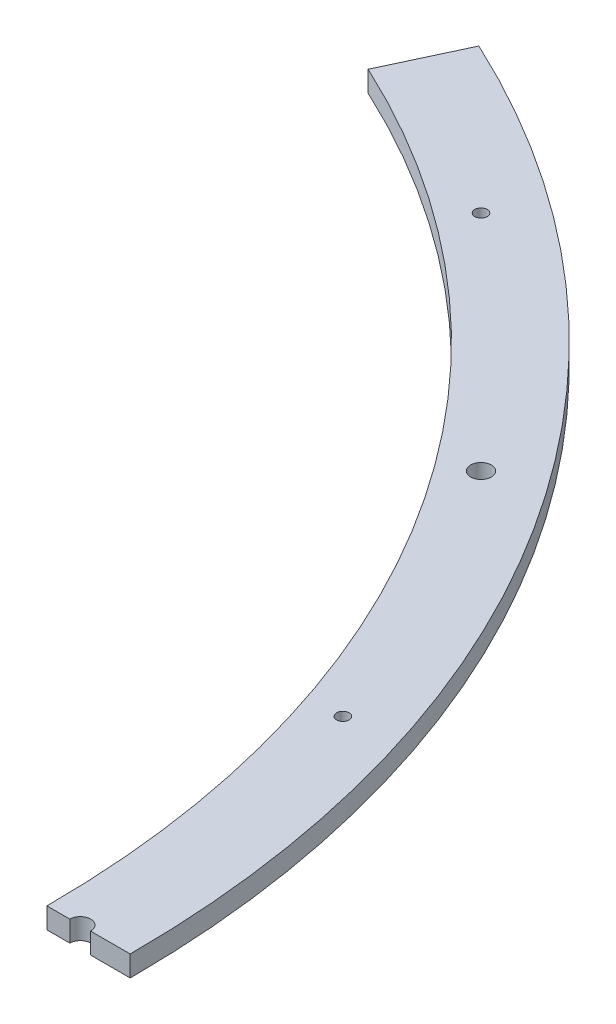
SolidWorks part; units mm, degrees
ref_plane "Front Plane" through (0, 0, 0) normal (0, 0, 1) x (1, 0, 0)
ref_plane "Top Plane" through (0, 0, 0) normal (0, 1, 0) x (1, 0, 0)
ref_plane "Right Plane" through (0, 0, 0) normal (1, 0, 0) x (0, 0, -1)
sketch "Sketch1" plane through (0, 0, 0) normal (0, 1, 0) x (1, 0, 0)
  circle A0 centre (0, 0) radius 254.5
  circle A1 centre (0, 0) radius 234.5
extrude "Boss-Extrude1" add sketch "Sketch1" along normal blind 5
sketch "Sketch2" plane through (0, 5, 0) normal (0, 1, 0) x (1, 0, 0)
  line L0 (-254.5, 0) -> (-226.6942, 0)
  line L1 (-226.6942, 0) -> (-226.6942, 60)
  line L2 (-226.6942, 60) -> (-254.5, 60)
  line L3 (-254.5, 60) -> (-254.5, 0)
  circle A0 centre (0, 0) radius 254.5 construction
  circle A1 centre (0, 0) radius 234.5 construction
  dimension "D1" = 60
extrude "Cut-Extrude1" cut sketch "Sketch2" against normal blind 5
mirror "Mirror1" about plane through (0, 0, 0) normal (0, 0, 1) of "Cut-Extrude1"
sketch "Sketch3" plane through (0, 5, 0) normal (0, 1, 0) x (1, 0, 0)
  circle A0 centre (242.5, 0) radius 2.5
  circle A1 centre (196.1866, -142.5379) radius 2.5
  circle A2 centre (74.9366, -230.6312) radius 2.5
  circle A3 centre (-74.9366, -230.6312) radius 2.5
  circle A4 centre (-196.1866, -142.5379) radius 2.5
  circle A5 centre (-242.5, 0) radius 2.5
  circle A6 centre (-196.1866, 142.5379) radius 2.5
  circle A7 centre (-74.9366, 230.6312) radius 2.5
  circle A8 centre (74.9366, 230.6312) radius 2.5
  circle A9 centre (196.1866, 142.5379) radius 2.5
  point P23 (0, 0)
  dimension "D1" = 242.5
  dimension "D2" = 10
extrude "Cut-Extrude2" cut sketch "Sketch3" against normal blind 5
sketch "Sketch4" plane through (0, 5, 0) normal (0, 1, 0) x (1, 0, 0)
  arc A0 (196.1866, 142.5379) -> (242.5, 0) centre (0, 0) cw
  circle A1 centre (230.6312, 74.9366) radius 1.5
  circle A2 centre (230.6312, -74.9366) radius 1.5
  circle A3 centre (142.5379, -196.1866) radius 1.5
  circle A4 centre (0, -242.5) radius 1.5
  circle A5 centre (-142.5379, -196.1866) radius 1.5
  circle A6 centre (-230.6312, -74.9366) radius 1.5
  circle A7 centre (-230.6312, 74.9366) radius 1.5
  circle A8 centre (-142.5379, 196.1866) radius 1.5
  circle A9 centre (0, 242.5) radius 1.5
  circle A10 centre (142.5379, 196.1866) radius 1.5
  circle A11 centre (230.6312, -74.9366) radius 1.5
  circle A12 centre (142.5379, -196.1866) radius 1.5
  circle A13 centre (0, -242.5) radius 1.5
  circle A14 centre (-142.5379, -196.1866) radius 1.5
  circle A15 centre (-230.6312, -74.9366) radius 1.5
  circle A16 centre (-230.6312, 74.9366) radius 1.5
  circle A17 centre (-142.5379, 196.1866) radius 1.5
  circle A18 centre (0, 242.5) radius 1.5
  circle A19 centre (142.5379, 196.1866) radius 1.5
  point P28 (0, 0)
  point P47 (0, 0)
  dimension "D1" = 10
  dimension "D2" = 10
extrude "Cut-Extrude3" cut sketch "Sketch4" against normal blind 5 contours A4 | A5 | A6 | A7 | A8 | A9 | A10 | A1 | A2 | A3
sketch "Sketch5" plane through (0, 5, 0) normal (0, 1, 0) x (1, 0, 0)
  line L1 (254.5, 0) -> (-396.7126, 0)
  line L2 (254.5, 0) -> (254.5, -357.2264)
  line L3 (254.5, -357.2264) -> (-396.7126, -357.2264)
  line L4 (-396.7126, 0) -> (-396.7126, -357.2264)
  arc A0 (-247.3262, -60) -> (-247.3262, 60) centre (0, 0) ccw construction
extrude "Cut-Extrude4" cut sketch "Sketch5" against normal blind 10
sketch "Sketch6" plane through (0, 5, 0) normal (0, 1, 0) x (1, 0, 0)
  line L0 (254.5, 0) -> (0, 0)
  line L1 (0, 0) -> (-127.25, 220.4035)
  line L2 (0, 0) -> (-254.5, 0)
  arc A0 (-127.25, 220.4035) -> (254.5, 0) centre (0, 0) cw
  arc A1 (254.5, 0) -> (-247.3262, 60) centre (0, 0) ccw construction
  arc A2 (-127.25, 220.4035) -> (-254.5, 0) centre (0, 0) ccw
  arc M5 (254.5, 0) -> (-247.3262, 60) centre (0, 0) ccw
  line M6 (-247.3262, 60) -> (-226.6942, 60)
  arc M7 (-226.6942, 60) -> (234.5, 0) centre (0, 0) cw
  circle M13 centre (-142.5379, 196.1866) radius 1.5
  circle M14 centre (-230.6312, 74.9366) radius 1.5
  circle M18 centre (-196.1866, 142.5379) radius 2.5
  dimension "D1" = 120
extrude "Cut-Extrude9" cut sketch "Sketch6" against normal blind 10 contours L1 M7 M5 M6 M13 M18 M14 | A2 L2 L1 M6 M7
sketch "Sketch7" plane through (0, 5, 0) normal (0, 1, 0) x (1, 0, 0)
  line L0 (254.5, 0) -> (0, 0)
  line L1 (0, 0) -> (107.5563, 230.6553)
  line L2 (0, 0) -> (-127.25, 220.4035)
  arc A0 (107.5563, 230.6553) -> (254.5, 0) centre (0, 0) cw
  arc A1 (254.5, 0) -> (-127.25, 220.4035) centre (0, 0) ccw construction
  line M4 (-127.25, 220.4035) -> (-117.25, 203.083)
  arc M5 (-117.25, 203.083) -> (234.5, 0) centre (0, 0) cw
  arc M9 (254.5, 0) -> (-127.25, 220.4035) centre (0, 0) ccw
  circle M12 centre (0, 242.5) radius 1.5
  circle M14 centre (74.9366, 230.6312) radius 2.5
  circle M15 centre (-74.9366, 230.6312) radius 2.5
  dimension "D1" = 65
extrude "Cut-Extrude11" cut sketch "Sketch7" against normal blind 10 contours L1 M5 M9 M4 M15 M14 M12 | L2 L1 M5
